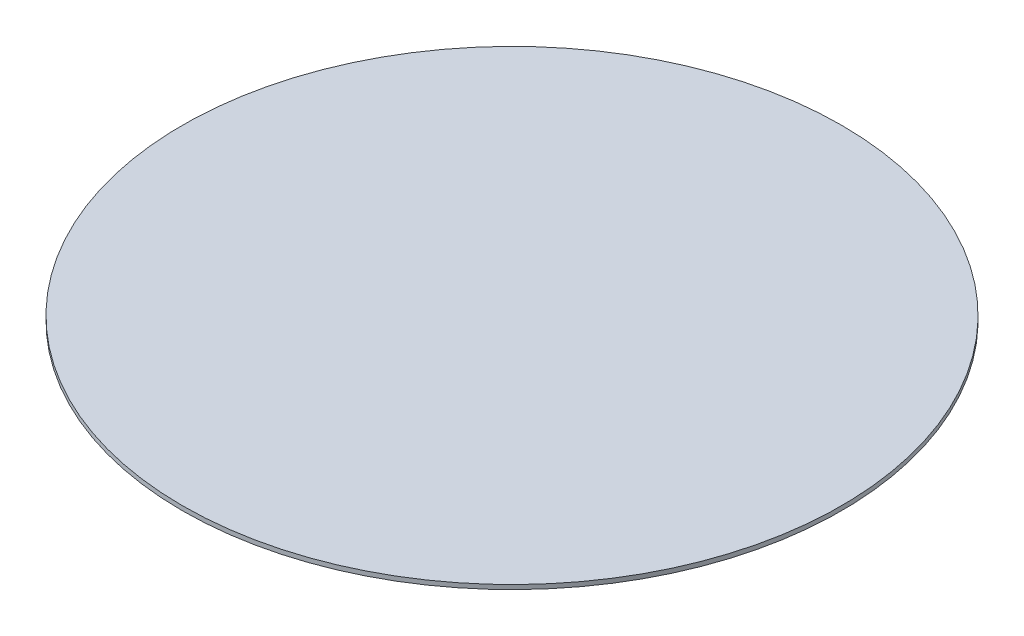
SolidWorks part; units mm, degrees
material "Stainless Steel (ferritic)"
ref_plane "Front Plane" through (0, 0, 0) normal (0, 0, 1) x (1, 0, 0)
ref_plane "Top Plane" through (0, 0, 0) normal (0, 1, 0) x (1, 0, 0)
ref_plane "Right Plane" through (0, 0, 0) normal (1, 0, 0) x (0, 0, -1)
sketch "Sketch1" plane through (0, 0, 0) normal (0, 0, 1) x (1, 0, 0)
  line L0 (-19.05, 0) -> (19.05, 0) construction
  line L1 (0, -0.0635) -> (0, 0.0635) construction
  line L2 (0, -0.0762) -> (0, 0.0762) construction
  line L3 (-19.05, 0.127) -> (-19.05, -0.127) construction
  point P4 (0, 0)
  point P8 (0, 0)
  point P10 (0, 0)
  point P13 (-19.05, 0)
  dimension "Diameter" = 38.1
  dimension "Wire Diameter" = 0.127
  dimension "Opening Size" = 0.1524
  dimension "Thickness" = 0.254
sketch "Sketch2" plane through (0, 0, 0) normal (0, 1, 0) x (1, 0, 0)
  line L0 (-19.05, 0) -> (19.05, 0) construction
  line L1 (0, 0.0762) -> (0, -0.0762) construction
  line L2 (0, -0.0762) -> (0, -0.2032) construction
  line L3 (0, 0.0762) -> (0, 0.2032) construction
  line L4 (-19.05, 19.05) -> (19.05, 19.05) construction
  circle A0 centre (0, 0) radius 19.05
  point P4 (0, 19.05)
  point P8 (0, 0)
  point P12 (0, 0.2032)
  point P13 (0, 0.0762)
  point P15 (0, -0.0762)
  point P16 (0, -0.2032)
  point P17 (19.05, 0)
  point P18 (-19.05, 0)
  point P19 (0, -19.05)
  point P23 (0, 19.05)
  point P24 (19.05, 19.05)
  point P25 (-19.05, 19.05)
  dimension "D1" = 0.1524
  dimension "D2" = 0.127
extrude "Boss-Extrude1" add sketch "Sketch2" along normal mid plane 0.254
equation "\"D1@Boss-Extrude1\" = \"Thickness@Sketch1\""
equation "\"D1@Sketch2\" = \"Opening Size@Sketch1\""
equation "\"D2@Sketch2\" = \"Wire Diameter@Sketch1\""
equation "\"Thickness@Sketch1\" = \"Wire Diameter@Sketch1\" * 2"
